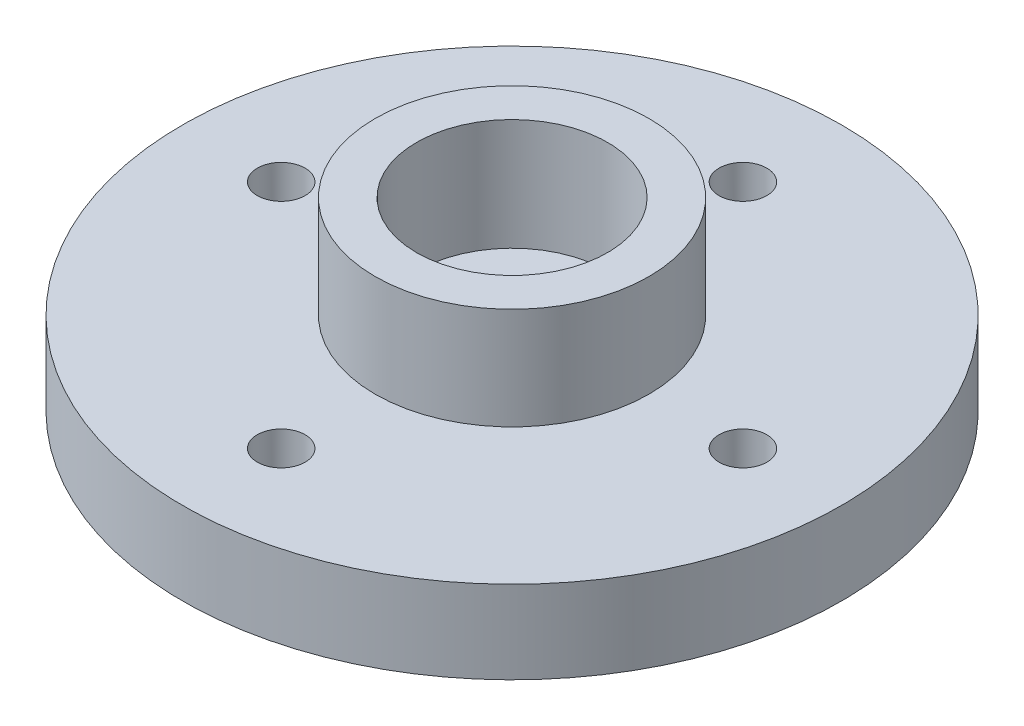
SolidWorks part; units mm, degrees
ref_plane "前视基准面" through (0, 0, 0) normal (0, 0, 1) x (1, 0, 0)
ref_plane "上视基准面" through (0, 0, 0) normal (0, 1, 0) x (1, 0, 0)
ref_plane "右视基准面" through (0, 0, 0) normal (1, 0, 0) x (0, 0, -1)
other "Configuration Table"
sketch "草图1" plane through (0, 0, 0) normal (0, 0, 1) x (1, 0, 0)
  line L0 (0, 0) -> (0, 9.0076) construction
  line L1 (0, -0.6) -> (-3.55, -0.6)
  line L2 (-3.55, -0.6) -> (-4.8367, 0)
  line L3 (-4.8367, 0) -> (-10.35, 0)
  line L4 (-10.35, 0) -> (-10.35, 2.6)
  line L5 (-10.35, 2.6) -> (-4.3, 2.6)
  line L6 (-4.3, 2.6) -> (-4.3, 5.8)
  line L7 (-4.3, 5.8) -> (0, 5.8)
  line L8 (0, 5.8) -> (0, -0.6)
  dimension "D1" = 20.7
  dimension "D2" = 8.6
  dimension "D3" = 2.6
  dimension "D4" = 3.2
  dimension "D5" = 7.1
  dimension "D6" = 0.6
  dimension "D7" = 25
revolve "旋转1" add sketch "草图1" angle 360 about L0
sketch "草图2" plane through (0, 5.8, 0) normal (0, 1, 0) x (1, 0, 0)
  circle A0 centre (0, 0) radius 3
  circle A1 centre (0, 0) radius 7.25 construction
  circle A2 centre (0, 7.25) radius 0.75
  circle A3 centre (7.25, 0) radius 0.75
  circle A4 centre (0, -7.25) radius 0.75
  circle A5 centre (-7.25, 0) radius 0.75
  dimension "D1" = 6
  dimension "D2" = 14.5
  dimension "D3" = 1.5
  dimension "D4" = 4
extrude "切除-拉伸1" cut sketch "草图2" against normal blind 10
sketch "草图3" plane through (0, 5.8, 0) normal (0, 1, 0) x (1, 0, 0)
  circle A0 centre (0, 0) radius 3 construction
  circle A1 centre (0, 0) radius 3
  circle A2 centre (0, 0) radius 1.5
  dimension "D1" = 3
extrude "凸台-拉伸1" add sketch "草图3" against normal up to surface (2.9 mm away) from offset 3.5 up to face at (0, -0.6, 3)
